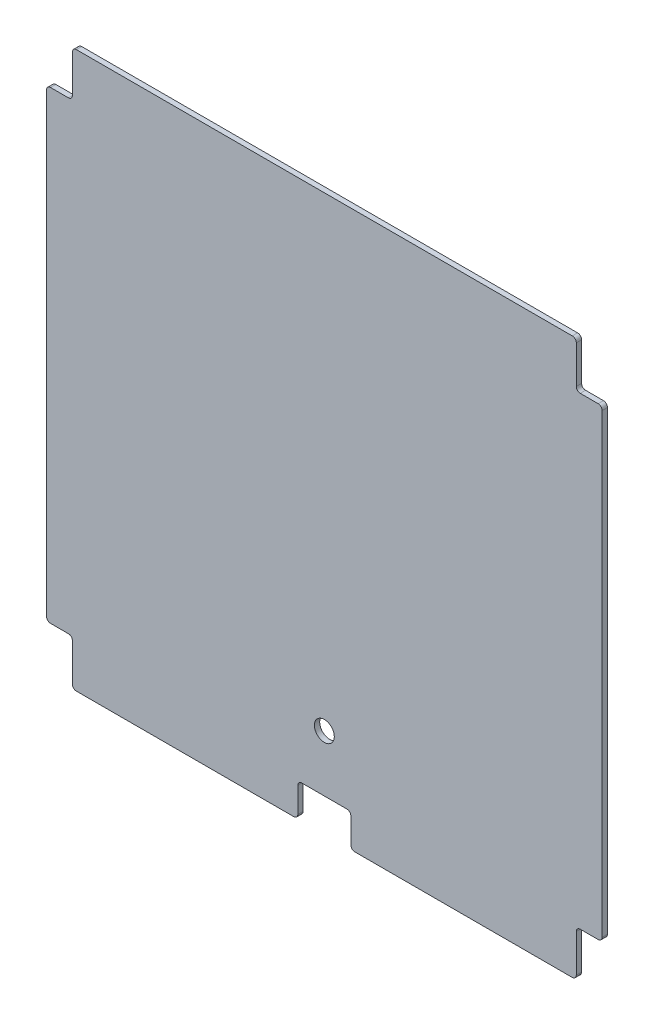
SolidWorks part; units mm, degrees
material "ABS PC"
ref_plane "Top Plane" through (0, 0, 0) normal (0, 0, 1) x (1, 0, 0)
ref_plane "Front Plane" through (0, 0, 0) normal (0, 1, 0) x (1, 0, 0)
ref_plane "Right Plane" through (0, 0, 0) normal (1, 0, 0) x (0, 0, -1)
sketch "Sketch1" plane through (0, 0, 0) normal (0, 0, 1) x (1, 0, 0)
  line L1 (-209.5, -209.5) -> (209.5, -209.5)
  line L2 (-209.5, -209.5) -> (-209.5, 209.5)
  line L3 (-209.5, 209.5) -> (209.5, 209.5)
  line L4 (209.5, -209.5) -> (209.5, 209.5)
  line L5 (-209.5, -209.5) -> (209.5, 209.5) construction
  line L6 (-209.5, 209.5) -> (209.5, -209.5) construction
  point P0 (0, 0)
  dimension "D1" = 419
  dimension "D2" = 419
extrude "base sheet" add sketch "Sketch1" along normal blind 4
sketch "Sketch2" plane through (0, 0, 4) normal (0, 0, 1) x (1, 0, 0)
  line L1 (-209.5, 209.5) -> (-190, 209.5)
  line L2 (-209.5, 209.5) -> (-209.5, 175)
  line L3 (-209.5, 175) -> (-190, 175)
  line L4 (-190, 209.5) -> (-190, 175)
  line L5 (209.5, 209.5) -> (190, 209.5)
  line L6 (209.5, 209.5) -> (209.5, 175)
  line L7 (209.5, 175) -> (190, 175)
  line L8 (190, 209.5) -> (190, 175)
  line L9 (-209.5, -209.5) -> (-190, -209.5)
  line L10 (-209.5, -209.5) -> (-209.5, -175)
  line L11 (-209.5, -175) -> (-190, -175)
  line L12 (-190, -209.5) -> (-190, -175)
  line L13 (209.5, -209.5) -> (190, -209.5)
  line L14 (209.5, -209.5) -> (209.5, -175)
  line L15 (209.5, -175) -> (190, -175)
  line L16 (190, -209.5) -> (190, -175)
  dimension "D1" = 19.5
  dimension "D2" = 34.5
  dimension "D3" = 19.5
  dimension "D4" = 34.5
  dimension "D5" = 19.5
  dimension "D6" = 19.5
  dimension "D7" = 34.5
  dimension "D8" = 34.5
extrude "belt cutouts" cut sketch "Sketch2" against normal through all
sketch "Sketch3" plane through (0, 0, 4) normal (0, 0, 1) x (1, 0, 0)
  line L0 (-190, -209.5) -> (190, -209.5) construction
  line L1 (-20, -209.5) -> (20, -209.5)
  line L2 (-20, -209.5) -> (-20, -184.5)
  line L3 (-20, -184.5) -> (20, -184.5)
  line L4 (20, -209.5) -> (20, -184.5)
  circle A0 centre (0, -142) radius 7.5
  dimension "D4" = 15
  dimension "D1" = 40
  dimension "D2" = 25
  dimension "D3" = 20
  dimension "D5" = 67.5
extrude "cable cutouts" cut sketch "Sketch3" against normal blind 4
fillet "Fillet1" radius 3 16 edges at (-190, 175, 2) (-209.5, 175, 2) (-190, 209.5, 2) (209.5, 175, 2) (190, 209.5, 2) (190, 175, 2) (190, -175, 2) (209.5, -175, 2) (190, -209.5, 2) (20, -209.5, 2) (20, -184.5, 2) (-20, -184.5, 2) (-20, -209.5, 2) (-190, -209.5, 2) (-190, -175, 2) (-209.5, -175, 2)
